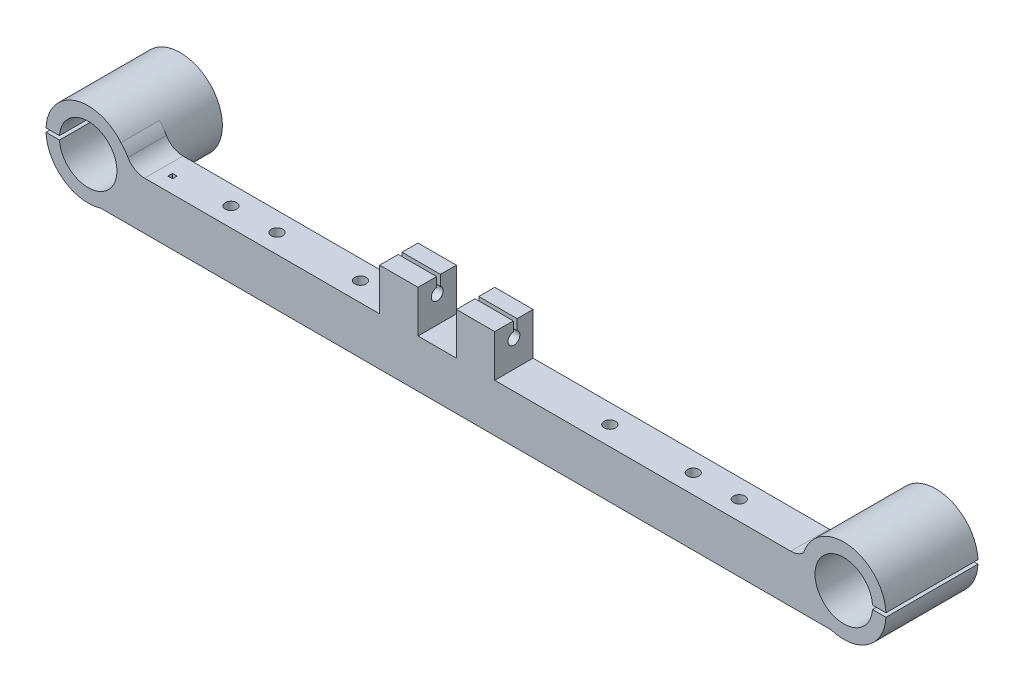
SolidWorks part; units mm, degrees
ref_plane "Front Plane" through (0, 0, 0) normal (0, 0, 1) x (1, 0, 0)
ref_plane "Top Plane" through (0, 0, 0) normal (0, 1, 0) x (1, 0, 0)
ref_plane "Right Plane" through (0, 0, 0) normal (1, 0, 0) x (0, 0, -1)
sketch "Sketch2" plane through (0, 0, 0) normal (0, 0, 1) x (1, 0, 0)
  line L0 (-98.5, 1.8316) -> (98.5, 1.8316) construction
  line L5 (-22.5, 3.8316) -> (-22.5, 14.8316)
  line L6 (-22.5, 14.8316) -> (-12.5, 14.8316)
  line L7 (-98.5, -8.6684) -> (98.5, -8.6684)
  line L10 (-87.0218, 3.8316) -> (-22.5, 3.8316)
  line L13 (7.5, 14.8316) -> (7.5, 3.8316)
  line L14 (7.5, 3.8316) -> (88.1922, 3.8316)
  line L15 (-12.5, 14.8316) -> (-12.5, 3.8316)
  line L16 (-12.5, 3.8316) -> (-2.5, 3.8316)
  line L17 (-2.5, 3.8316) -> (-2.5, 14.8316)
  line L18 (-2.5, 14.8316) -> (7.5, 14.8316)
  circle A0 centre (-98.5, 1.8316) radius 7.5
  circle A1 centre (98.5, 1.8316) radius 7.5
  arc A2 (-98.5, 12.3316) -> (-98.5, -8.6684) centre (-98.5, 1.8316) ccw
  arc A3 (98.5, -8.6684) -> (98.5, 12.3316) centre (98.5, 1.8316) ccw
  arc A4 (-98.5, 12.3316) -> (-87.0218, 3.8316) centre (-98.5, 0.3316) cw
  arc A5 (98.5, 12.3316) -> (88.1922, 3.8316) centre (98.5, 1.8316) ccw
  point P0 (0, 0)
  point P10 (0, 1.8316)
  dimension "D1" = 15
  dimension "D3" = 3
  dimension "D9" = 12
  dimension "D2" = 197
  dimension "D4" = 12.5
  dimension "D5" = 22.5
  dimension "D6" = 30
  dimension "D7" = 11
  dimension "D8" = 10
extrude "Boss-Extrude1" add sketch "Sketch2" along normal blind 10
sketch "Sketch8" plane through (0, 3.8316, 0) normal (0, 1, 0) x (1, 0, 0)
  line L0 (-87.0218, -10) -> (88.1922, -10) construction
  line L1 (-87.0218, -10) -> (-87.0218, 0) construction
  line L2 (-32.5028, -5) -> (32.4972, -5) construction
  line L3 (-54.2568, -5) -> (-66.2568, -5) construction
  line L4 (66.2452, -5) -> (54.2452, -5) construction
  line L5 (88.1922, -10) -> (88.1922, 0) construction
  circle A0 centre (-66.2568, -5) radius 1.5
  circle A1 centre (-54.2568, -5) radius 1.5
  circle A2 centre (-32.5028, -5) radius 1.5
  circle A3 centre (32.4972, -5) radius 1.5
  circle A4 centre (54.2452, -5) radius 1.5
  circle A5 centre (66.2452, -5) radius 1.5
  point P16 (0.5852, -10)
  point P19 (-87.0218, -5)
  point P21 (60.2452, -5)
  dimension "D6" = 3
  dimension "D1" = 12
  dimension "D2" = 12
  dimension "D3" = 59.66
  dimension "D4" = 54.842
  dimension "D5" = 65
  dimension "D7" = 55.695
fillet "Fillet1" radius 5 1 edges at (88.1922, 3.8316, 5)
sketch "Sketch3" plane through (0, 0, 10) normal (0, 0, 1) x (1, 0, 0)
  circle A0 centre (-98.5, 1.8316) radius 7.5
  circle A1 centre (-98.5, 1.8316) radius 11
  dimension "D1" = 15
  dimension "D2" = 22
extrude "Boss-Extrude2" add sketch "Sketch3" against normal blind 24
mirror "Mirror1" about plane through (0, 0, 0) normal (1, 0, 0) of "Boss-Extrude2"
sketch "Sketch4" plane through (-22.5, 0, 0) normal (-1, 0, 0) x (0, 0, 1)
  line L0 (10, 14.8316) -> (0, 14.8316) construction
  circle A0 centre (5, 10.8058) radius 1.55
  point P4 (5, 14.8316)
  dimension "D1" = 3.1
extrude "Cut-Extrude1" cut sketch "Sketch4" against normal up to surface (30 mm away) up to face at (7.5, 9.3316, 5)
ref_plane "Plane1" through (110, 0, 0) normal (1, 0, 0) x (0, 0, -1)
sketch "Sketch6" plane through (110, 0, 0) normal (1, 0, 0) x (0, 0, -1)
  line L0 (-10, 12.8316) -> (-10, -9.1684) construction
  line L1 (-17.1743, 1.3316) -> (19.9382, 1.3316)
  line L2 (-17.1743, 1.3316) -> (-17.1743, 2.3316)
  line L3 (-17.1743, 2.3316) -> (19.9382, 2.3316)
  line L4 (19.9382, 1.3316) -> (19.9382, 2.3316)
  line L5 (-17.1743, 1.3316) -> (19.9382, 2.3316) construction
  line L6 (-17.1743, 2.3316) -> (19.9382, 1.3316) construction
  point P0 (1.3819, 1.8316)
  point P7 (-10, 1.8316)
  point P8 (-17.1743, 1.8316)
  dimension "D1" = 1
extrude "Cut-Extrude3" cut sketch "Sketch6" against normal blind 10
mirror "Mirror2" about plane through (0, 0, 0) normal (1, 0, 0) of "Cut-Extrude3"
sketch "Sketch7" plane through (0, 14.8316, 0) normal (0, 1, 0) x (1, 0, 0)
  line L1 (-26.2478, -5.1544) -> (10.4895, -5.1544)
  line L2 (-26.2478, -5.1544) -> (-26.2478, -4.1544)
  line L3 (-26.2478, -4.1544) -> (10.4895, -4.1544)
  line L4 (10.4895, -5.1544) -> (10.4895, -4.1544)
  line L5 (-26.2478, -5.1544) -> (10.4895, -4.1544) construction
  line L6 (-26.2478, -4.1544) -> (10.4895, -5.1544) construction
  dimension "D1" = 1
extrude "Cut-Extrude4" cut sketch "Sketch7" against normal blind 3
fillet "Fillet2" radius 5 1 edges at (-87.0218, 3.8316, 5)
extrude "Cut-Extrude5" cut sketch "Sketch8" against normal blind 7
sketch "Sketch9" plane through (0, 3.8316, 0) normal (0, 1, 0) x (1, 0, 0)
  line L1 (-79.9928, -6.4888) -> (-81.2347, -6.4888)
  line L2 (-79.9928, -6.4888) -> (-79.9928, -5.3006)
  line L3 (-79.9928, -5.3006) -> (-81.2347, -5.3006)
  line L4 (-81.2347, -6.4888) -> (-81.2347, -5.3006)
extrude "Cut-Extrude6" cut sketch "Sketch9" against normal blind 1
